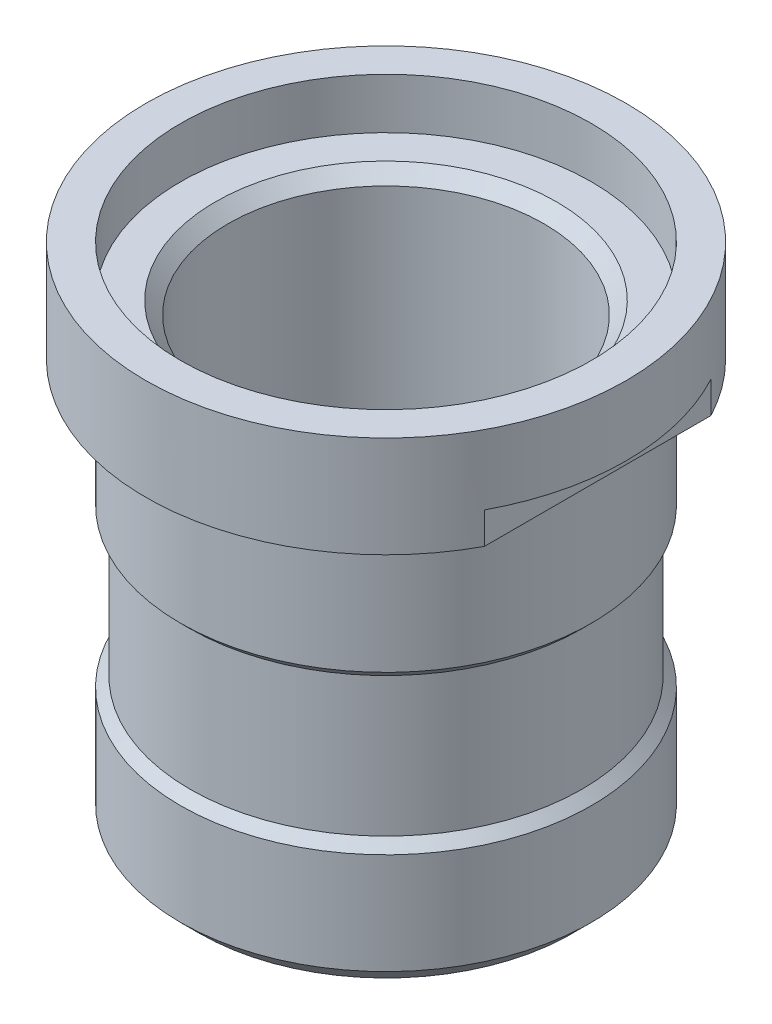
SolidWorks part; units mm, degrees
ref_plane "Front Plane" through (0, 0, 0) normal (0, 0, 1) x (1, 0, 0)
ref_plane "Top Plane" through (0, 0, 0) normal (0, 1, 0) x (1, 0, 0)
ref_plane "Right Plane" through (0, 0, 0) normal (1, 0, 0) x (0, 0, -1)
sketch "Sketch1" plane through (0, 0, 0) normal (0, 0, 1) x (1, 0, 0)
  line L0 (0, 0) -> (0, 80) construction
  line L1 (-32.5, 80) -> (-32.5, 72)
  line L2 (-32.5, 72) -> (-27, 72)
  line L3 (-25, 70) -> (-25, 0)
  line L4 (-38, 80) -> (-38, 64)
  line L5 (-38, 64) -> (-32.5, 64)
  line L6 (-32.5, 64) -> (-32.5, 44)
  line L7 (-32.5, 0) -> (-32.5, 19)
  line L8 (-31, 42.5) -> (-31, 20.5)
  line L9 (-31, 42.5) -> (-32.5, 44)
  line L10 (-31, 20.5) -> (-32.5, 19)
  line L11 (-32.5, 0) -> (-25, 0)
  line L12 (-38, 80) -> (-32.5, 80)
  line L13 (-27, 72) -> (-25, 70)
  point P7 (-25, 72)
  dimension "D1" = 80
  dimension "D2" = 65
  dimension "D3" = 50
  dimension "D4" = 8
  dimension "D5" = 76
  dimension "D6" = 16
  dimension "D7" = 65
  dimension "D8" = 20
  dimension "D9" = 62
  dimension "D10" = 19
  dimension "D11" = 45
  dimension "D12" = 45
  dimension "D13" = 2
  dimension "D14" = 45
revolve "Revolve1" add sketch "Sketch1" angle 360 about L0
sketch "Sketch2" plane through (0, 80, 0) normal (0, 1, 0) x (1, 0, 0)
  line L1 (33.5, 35.8098) -> (53.5252, 35.8098)
  line L2 (33.5, 35.8098) -> (33.5, -37.4589)
  line L3 (33.5, -37.4589) -> (53.5252, -37.4589)
  line L4 (53.5252, 35.8098) -> (53.5252, -37.4589)
  dimension "D1" = 33.5
extrude "Cut-Extrude1" cut sketch "Sketch2" against normal through all from offset 11 offset against normal yes
chamfer "Chamfer1" distance 3 angle 45 1 edges at (0, 0, -32.5)
